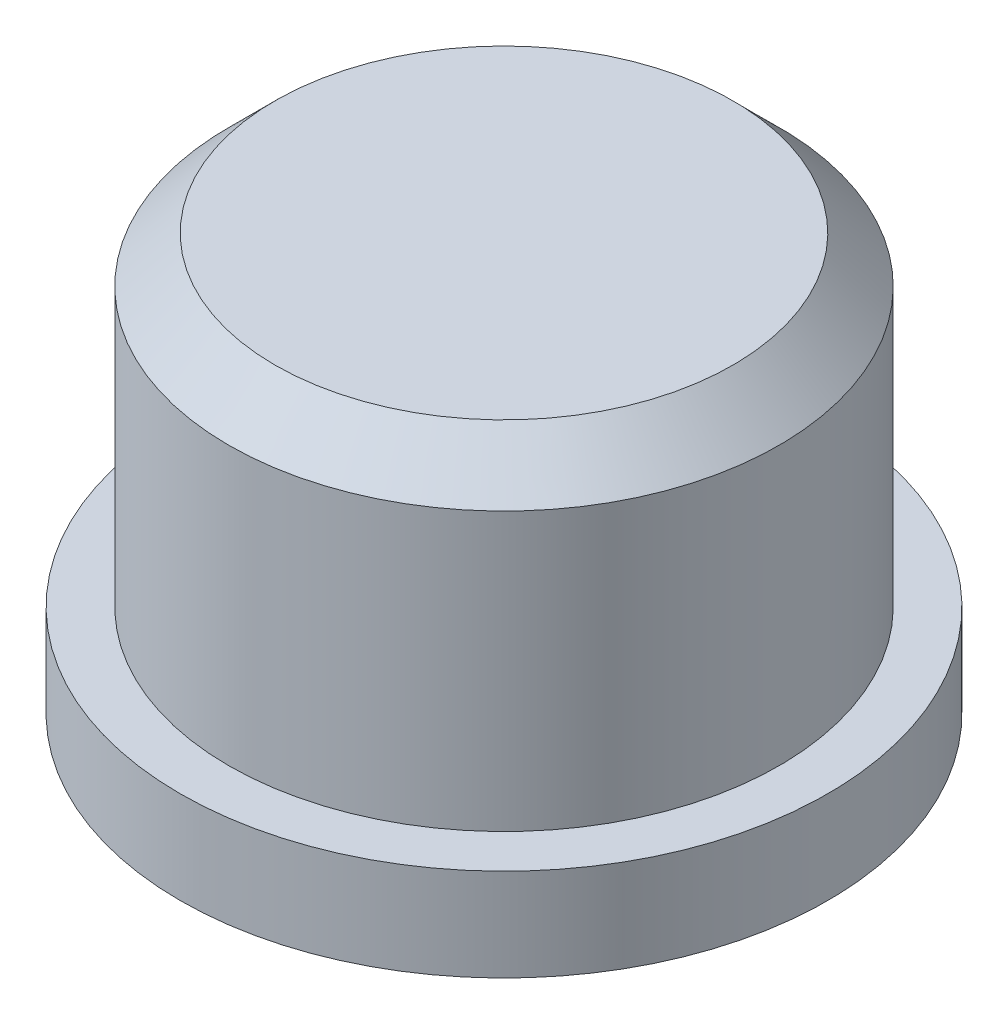
SolidWorks part; units mm, degrees
ref_plane "Front Plane" through (0, 0, 0) normal (0, 0, 1) x (1, 0, 0)
ref_plane "Top Plane" through (0, 0, 0) normal (0, 1, 0) x (1, 0, 0)
ref_plane "Right Plane" through (0, 0, 0) normal (1, 0, 0) x (0, 0, -1)
sketch "Sketch1" plane through (0, 0, 0) normal (0, 1, 0) x (1, 0, 0)
  circle A0 centre (0, 0) radius 7
  dimension "D1" = 14
extrude "Boss-Extrude1" add sketch "Sketch1" along normal blind 2
sketch "Sketch2" plane through (0, 2, 0) normal (0, 1, 0) x (1, 0, 0)
  circle A0 centre (0, 0) radius 5.95
  dimension "D1" = 11.9
extrude "Boss-Extrude2" add sketch "Sketch2" along normal blind 7
sketch "Sketch3" plane through (0, 0, 0) normal (0, -1, 0) x (1, 0, 0)
  circle A1 centre (0, 0) radius 3.5
  dimension "D1" = 7
extrude "Cut-Extrude1" cut sketch "Sketch3" against normal blind 1.8
chamfer "Chamfer1" distance 1 angle 45 1 edges at (0, 9, 5.95)
